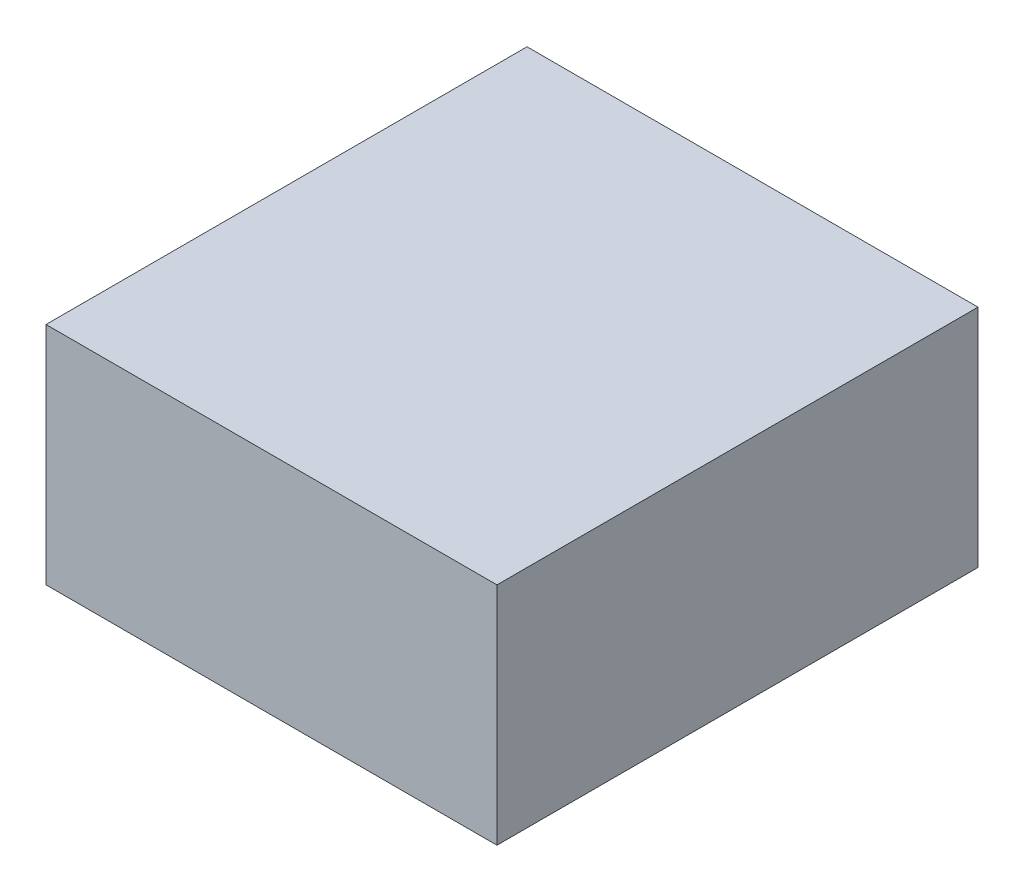
SolidWorks part; units mm, degrees
ref_plane "前视基准面" through (0, 0, 0) normal (0, 0, 1) x (1, 0, 0)
ref_plane "上视基准面" through (0, 0, 0) normal (0, 1, 0) x (1, 0, 0)
ref_plane "右视基准面" through (0, 0, 0) normal (1, 0, 0) x (0, 0, -1)
sketch "草图1" plane through (0, 0, 0) normal (0, 0, 1) x (1, 0, 0)
  line L1 (150, -75) -> (-150, -75)
  line L2 (150, -75) -> (150, 75)
  line L3 (150, 75) -> (-150, 75)
  line L4 (-150, -75) -> (-150, 75)
  line L5 (150, -75) -> (-150, 75) construction
  line L6 (150, 75) -> (-150, -75) construction
  point P0 (0, 0)
  dimension "D1" = 300
  dimension "D2" = 150
extrude "凸台-拉伸1" add sketch "草图1" along normal mid plane 320
sketch "草图2" plane through (-150, 0, 0) normal (-1, 0, 0) x (0, 0, 1)
  line L0 (-160, -30) -> (160, -30) construction
  line L1 (-160, 75) -> (-160, -75) construction
  line L2 (160, 75) -> (160, -75) construction
  text T0 "   工控机" font "Century Gothic" height 50
  dimension "D1" = 30
extrude "切除-拉伸1" cut sketch "草图2" against normal blind 1
